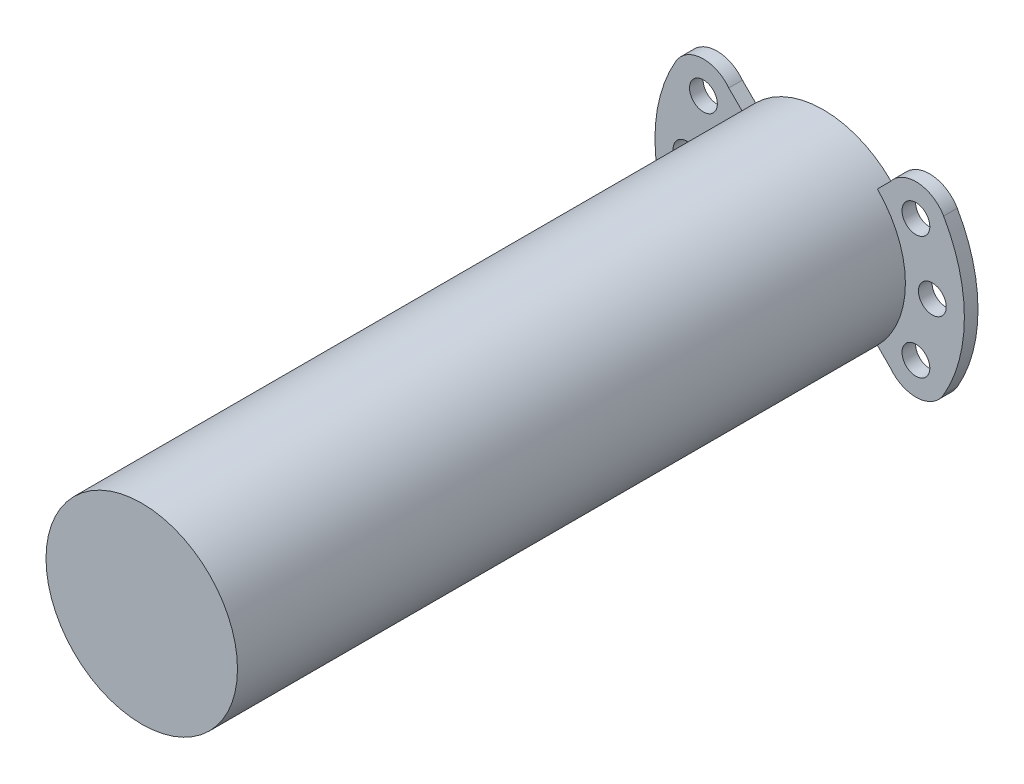
SolidWorks part; units mm, degrees
material "6061-T6 (SS)"
ref_plane "Front Plane" through (0, 0, 0) normal (0, 0, 1) x (1, 0, 0)
ref_plane "Top Plane" through (0, 0, 0) normal (0, 1, 0) x (1, 0, 0)
ref_plane "Right Plane" through (0, 0, 0) normal (1, 0, 0) x (0, 0, -1)
sketch "Sketch1" plane through (0, 0, 0) normal (0, 0, 1) x (1, 0, 0)
  circle A0 centre (0, 0) radius 17.526
  circle A1 centre (0, 0) radius 21.082
  dimension "D1" = 3.556
  dimension "D2" = 35.052
  dimension "D3" = 42.164
extrude "Boss-Extrude1" add sketch "Sketch1" along normal blind 254
sketch "Sketch2" plane through (0, 0, 0) normal (0, 0, -1) x (-1, 0, 0)
  circle A0 centre (0, 0) radius 21.082
extrude "Boss-Extrude2" add sketch "Sketch2" along normal blind 6.35
sketch "Sketch3" plane through (0, 0, 254) normal (0, 0, 1) x (1, 0, 0)
  circle A0 centre (0, 0) radius 25.8684
extrude "Cut-Extrude1" cut sketch "Sketch3" against normal blind 127
sketch "Sketch4" plane through (0, 0, 127) normal (0, 0, 1) x (1, 0, 0)
  circle A0 centre (0, 0) radius 19.0911
  circle A1 centre (0, 0) radius 34.925
  dimension "D1" = 69.85
extrude "Boss-Extrude3" add sketch "Sketch4" against normal blind 3.175
sketch "Sketch5" plane through (0, 0, 127) normal (0, 0, 1) x (1, 0, 0)
  line L0 (0, 0) -> (0, 17.526)
  line L1 (0, 17.526) -> (0, 34.925)
  circle A0 centre (0, 0) radius 17.526 construction
  circle A3 centre (0, 0) radius 34.925 construction
  circle A4 centre (0, 28.575) radius 3.175
  circle A5 centre (0, 28.575) radius 6.35
  dimension "D1" = 6.35
  dimension "D2" = 12.7
  dimension "D3" = 28.575
extrude "Cut-Extrude2" cut sketch "Sketch5" against normal through all contours L1 A4 | L1 A4
pattern_circular "CirPattern1" count 12 every 30 about axis through (0, 0, 0) along (0, 0, 1) of "Cut-Extrude2"
sketch "Sketch6" plane through (0, 0, -6.35) normal (0, 0, -1) x (-1, 0, 0)
  circle A0 centre (0, 0) radius 21.082
extrude "Cut-Extrude3" cut sketch "Sketch6" against normal blind 6.35
sketch "Sketch7" plane through (0, 0, 0) normal (0, 0, -1) x (-1, 0, 0)
  circle A0 centre (0, 0) radius 21.082
extrude "Boss-Extrude4" add sketch "Sketch7" against normal blind 6.35
sketch "Sketch8" plane through (0, 0, 127) normal (0, 0, 1) x (1, 0, 0)
  line L0 (14.2875, 24.7467) -> (8.763, 15.178)
  line L1 (8.763, 15.178) -> (-14.2875, -24.7467)
  line L2 (-14.2875, -24.7467) -> (-17.4625, -30.2459)
  line L3 (14.2875, 24.7467) -> (17.4625, 30.2459)
  line L4 (-24.7467, 14.2875) -> (24.7467, -14.2875)
  line L5 (24.7467, 14.2875) -> (-24.7467, -14.2875)
  line L6 (0, 0) -> (20.2056, 20.2056)
  line L7 (0, 0) -> (20.2056, -20.2056)
  line L8 (0, 0) -> (-14.2875, 24.7467)
  line L9 (0, 0) -> (-20.2056, 20.2056)
  line L10 (0, 0) -> (-20.2056, -20.2056)
  circle A0 centre (0, 0) radius 34.925
  circle A1 centre (0, 0) radius 17.526
  circle A2 centre (0, 0) radius 28.575
  circle A3 centre (24.7467, 14.2875) radius 7.4596
  circle A4 centre (24.7467, -14.2875) radius 7.4596
  circle A5 centre (-24.7467, -14.2875) radius 7.4596
  circle A6 centre (-24.7467, 14.2875) radius 7.4596
  circle A7 centre (0, 0) radius 36.0346
  circle A8 centre (0, 0) radius 21.082
  circle M4 centre (-14.2875, -24.7467) radius 3.175
  circle M5 centre (0, -28.575) radius 3.175
  circle M6 centre (14.2875, -24.7467) radius 3.175
  circle M10 centre (14.2875, 24.7467) radius 3.175
  circle M11 centre (-14.2875, 24.7467) radius 3.175
  circle M12 centre (0, 28.575) radius 3.175
  circle M14 centre (0, 0) radius 34.925
  dimension "D1" = 42.164
extrude "Cut-Extrude5" cut sketch "Sketch8" against normal through all contours A8 L0 A2 L8 M10 M12 M11 | A6 A2 L3 M11 M12 M10 M14 | A8 L8 A2 A6 L9 M11 | A8 L6 A3 A2 L0 M10 | A3 L3 A2 M14 M10 | A4 A2 L2 M6 M5 M4 M14 | A8 L1 A2 A4 L7 M4 M5 M6 | A8 L10 A5 A2 L1 M4 | A5 L2 A2 M14 M4 | A0
sketch "Sketch11" plane through (0, 0, 127) normal (0, 0, 1) x (1, 0, 0)
  circle A0 centre (24.7467, 14.2875) radius 7.4596
  circle A1 centre (0, 0) radius 36.0346
  circle A2 centre (24.7467, -14.2875) radius 7.4596
  circle A3 centre (-24.7467, -14.2875) radius 7.4596
  circle A4 centre (-24.7467, 14.2875) radius 7.4596
  arc M8 (27.8541, -21.069) -> (27.8541, 21.069) centre (0, 0) ccw
  arc M14 (-27.8541, 21.069) -> (-27.8541, -21.069) centre (0, 0) ccw
extrude "Boss-Extrude5" add sketch "Sketch11" against normal up to surface (3.175 mm away) contours A4 A1 A3 M14 | A4 M14 | A3 M14 | A2 M8 | A2 A1 A0 M8 | A0 M8
sketch "Sketch12" plane through (0, 0, 127) normal (0, 0, 1) x (1, 0, 0)
  circle A0 centre (0, 0) radius 21.082
  circle A1 centre (0, 0) radius 17.907
  dimension "D1" = 35.814
sketch "Sketch13" plane through (0, 0, 127) normal (0, 0, 1) x (1, 0, 0)
  circle A0 centre (0, 0) radius 18.0848
  circle A2 centre (0, 0) radius 20.701
  dimension "D1" = 36.1696
  dimension "D2" = 41.402
extrude "Cut-Extrude6" cut sketch "Sketch13" against normal blind 1.016
sketch "Sketch14" plane through (0, 0, 127) normal (0, 0, 1) x (1, 0, 0)
  circle A0 centre (0, 0) radius 22.3012
  circle A1 centre (0, 0) radius 20.701 construction
  circle A2 centre (0, 0) radius 20.701
  dimension "D1" = 1.6002
extrude "Boss-Extrude6" add sketch "Sketch14" against normal up to surface (3.175 mm away) up to face at (27.9217, -14.2875, 123.825)
sketch "Sketch15" plane through (0, 0, 123.825) normal (0, 0, -1) x (-1, 0, 0)
  circle A0 centre (0, 0) radius 39.9365
  circle M2 centre (24.7467, 14.2875) radius 3.175
  circle M3 centre (28.575, 0) radius 3.175
  circle M4 centre (24.7467, -14.2875) radius 3.175
  line M5 (18.8286, 18.8286) -> (15.7693, 15.7693)
  arc M6 (15.7693, 15.7693) -> (-15.7693, 15.7693) centre (0, 0) ccw
  line M7 (-15.7693, 15.7693) -> (-18.8286, 18.8286)
  arc M8 (-18.8286, 18.8286) -> (-31.2069, 18.0173) centre (-24.7467, 14.2875) ccw
  arc M9 (-31.2069, 18.0173) -> (-31.2069, -18.0173) centre (0, 0) ccw
  arc M10 (-31.2069, -18.0173) -> (-18.8286, -18.8286) centre (-24.7467, -14.2875) ccw
  line M11 (-18.8286, -18.8286) -> (-15.7693, -15.7693)
  arc M12 (-15.7693, -15.7693) -> (15.7693, -15.7693) centre (0, 0) ccw
  line M13 (15.7693, -15.7693) -> (18.8286, -18.8286)
  arc M14 (18.8286, -18.8286) -> (31.2069, -18.0173) centre (24.7467, -14.2875) ccw
  arc M15 (31.2069, -18.0173) -> (31.2069, 18.0173) centre (0, 0) ccw
  arc M16 (31.2069, 18.0173) -> (18.8286, 18.8286) centre (24.7467, 14.2875) ccw
  circle M17 centre (0, 0) radius 21.082
  circle M18 centre (-24.7467, -14.2875) radius 3.175
  circle M19 centre (-28.575, 0) radius 3.175
  circle M20 centre (-24.7467, 14.2875) radius 3.175
extrude "Boss-Extrude7" add sketch "Sketch15" along normal up to surface (123.825 mm away) contours M16 M5 M6 M7 M8 M9 M10 M11 M12 M13 M14 M15 M3 M18 M20 M19 M17 M4 M2 up to face at (-21.082, 0, 0)
sketch "Sketch16" plane through (0, 0, 0) normal (0.7071, 0.7071, 0) x (0.7071, -0.7071, 0)
  line L0 (-24.4644, -127) -> (-24.4644, -123.825)
  line L1 (-22.3012, -127) -> (-26.6277, -127) construction
  dimension "D1" = 3.175
ref_plane "Plane1" through (0, 0, 123.825) normal (0, 0, 1) x (1, 0, 0)
sketch "Sketch17" plane through (0, 0, 123.825) normal (0, 0, 1) x (1, 0, 0)
  circle A0 centre (0, 0) radius 47.4648
  circle A1 centre (0, 0) radius 22.3012
  arc A2 (15.7693, 15.7693) -> (-15.7693, 15.7693) centre (0, 0) ccw construction
  dimension "D1" = 0
extrude "Cut-Extrude7" cut sketch "Sketch17" against normal offset from surface (120.65 mm away) 3.175 up to face at (21.5717, 14.2875, 0)
sketch "Sketch18" plane through (0, 0, 127) normal (0, 0, 1) x (1, 0, 0)
  circle A0 centre (0, 0) radius 17.526
extrude "Cut-Extrude8" cut sketch "Sketch18" against normal through all
sketch "Sketch19" plane through (0, 0, 0) normal (0, 0, -1) x (-1, 0, 0)
  circle A0 centre (0, 0) radius 18.0848
  circle A1 centre (0, 0) radius 20.701
  dimension "D1" = 41.402
  dimension "D2" = 36.1696
extrude "Cut-Extrude9" cut sketch "Sketch19" against normal blind 1.016
sketch "Sketch20" plane through (0, 0, 127) normal (0, 0, 1) x (1, 0, 0)
  circle A0 centre (0, 0) radius 22.3012
  circle A1 centre (0, 0) radius 44.7953
extrude "Cut-Extrude10" cut sketch "Sketch20" against normal blind 12.7
sketch "Sketch22" plane through (0, 0, 127) normal (0, 0, 1) x (1, 0, 0)
  circle A0 centre (0, 0) radius 22.3012
  circle A1 centre (0, 0) radius 17.526
  circle A2 centre (0, 0) radius 20.701
  circle A3 centre (0, 0) radius 18.0848
extrude "Boss-Extrude8" add sketch "Sketch22" along normal blind 31.75 contours A3 A1
sketch "Sketch23" plane through (0, 0, 125.984) normal (0, 0, 1) x (1, 0, 0)
  circle A0 centre (0, 0) radius 18.0848
  circle A1 centre (0, 0) radius 20.701
extrude "Boss-Extrude9" add sketch "Sketch23" along normal up to surface (32.766 mm away) up to face at (22.3012, 0, 158.75)
sketch "Sketch24" plane through (0, 0, 158.75) normal (0, 0, 1) x (1, 0, 0)
  circle A0 centre (0, 0) radius 17.526
extrude "Boss-Extrude10" add sketch "Sketch24" against normal blind 6.35
sketch "Sketch25" plane through (0, 0, 0) normal (0, 0, -1) x (-1, 0, 0)
  circle A0 centre (-24.7467, 14.2875) radius 3.2385
  circle A1 centre (-28.575, 0) radius 3.2385
  circle A4 centre (-24.7467, -14.2875) radius 3.2385
  circle A5 centre (24.7467, 14.2875) radius 3.2385
  circle A7 centre (28.575, 0) radius 3.2385
  circle A9 centre (24.7467, -14.2875) radius 3.2385
  dimension "D1" = 6.477
  dimension "D2" = 6.477
  dimension "D3" = 6.477
  dimension "D4" = 6.477
  dimension "D5" = 6.477
  dimension "D6" = 6.477
extrude "Cut-Extrude11" cut sketch "Sketch25" against normal through all
